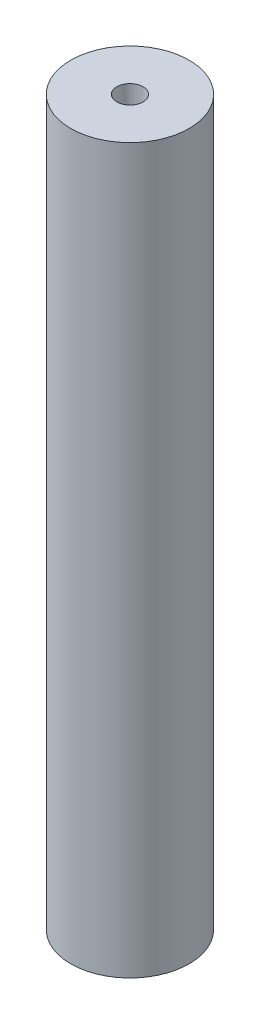
SolidWorks part; units mm, degrees
ref_plane "前视基准面" through (0, 0, 0) normal (0, 0, 1) x (1, 0, 0)
ref_plane "上视基准面" through (0, 0, 0) normal (0, 1, 0) x (1, 0, 0)
ref_plane "右视基准面" through (0, 0, 0) normal (1, 0, 0) x (0, 0, -1)
other "Configuration Table"
sketch "草图1" plane through (0, 0, 0) normal (0, 1, 0) x (1, 0, 0)
  circle A0 centre (0, 0) radius 2
  circle A1 centre (0, 0) radius 9
extrude "凸台-拉伸1" add sketch "草图1" along normal blind 110 contours A0 | A1
